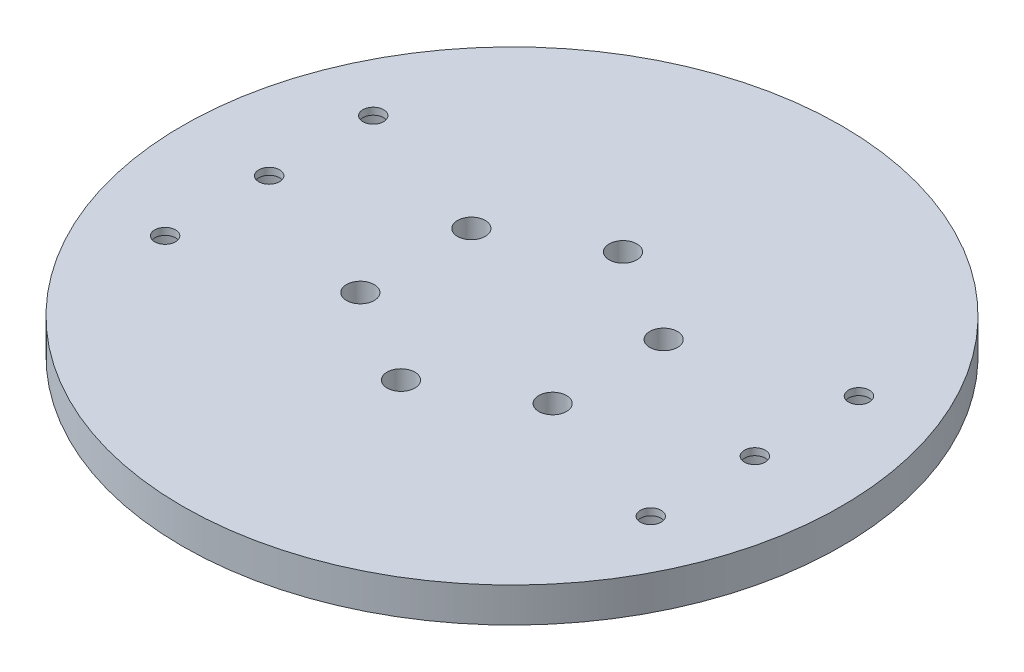
SolidWorks part; units mm, degrees
ref_plane "Alzado" through (0, 0, 0) normal (0, 0, 1) x (1, 0, 0)
ref_plane "Planta" through (0, 0, 0) normal (0, 1, 0) x (1, 0, 0)
ref_plane "Vista lateral" through (0, 0, 0) normal (1, 0, 0) x (0, 0, -1)
sketch "Croquis1" plane through (0, 0, 0) normal (0, 1, 0) x (1, 0, 0)
  circle A0 centre (0, 0) radius 24.5
  dimension "D1" = 49
extrude "Saliente-Extruir1" add sketch "Croquis1" along normal blind 4
sketch "Croquis2" plane through (0, 4, 0) normal (0, 1, 0) x (1, 0, 0)
  circle A0 centre (0, 0) radius 16 construction
  circle A1 centre (0, 16) radius 2
  dimension "D1" = 32
  dimension "D2" = 4
extrude "Cortar-Extruir1" cut sketch "Croquis2" against normal through all
pattern_circular "MatrizC1" count 6 over 360 about axis through (0, 0, 0) along (0, 1, 0) of "Cortar-Extruir1"
sketch "Croquis3" plane through (0, 4, 0) normal (0, 1, 0) x (1, 0, 0)
  circle A1 centre (0, 0) radius 47.5
  circle A2 centre (13.8564, 8) radius 2 construction
  circle A3 centre (13.8564, -8) radius 2 construction
  circle A4 centre (0, -16) radius 2 construction
  circle A5 centre (-13.8564, -8) radius 2 construction
  circle A6 centre (-13.8564, 8) radius 2 construction
  circle A7 centre (0, 16) radius 2 construction
  circle A8 centre (13.8564, 8) radius 2
  circle A9 centre (13.8564, -8) radius 2
  circle A10 centre (0, -16) radius 2
  circle A11 centre (-13.8564, -8) radius 2
  circle A12 centre (-13.8564, 8) radius 2
  circle A13 centre (0, 16) radius 2
  dimension "D1" = 95
extrude "Saliente-Extruir2" add sketch "Croquis3" along normal blind 5
sketch "Croquis4" plane through (0, 9, 0) normal (0, 1, 0) x (1, 0, 0)
  line L1 (-30, -20) -> (30, -20)
  line L2 (-30, -20) -> (-30, 20)
  line L3 (-30, 20) -> (30, 20)
  line L4 (30, -20) -> (30, 20)
  line L5 (-30, -20) -> (30, 20) construction
  line L6 (-30, 20) -> (30, -20) construction
  point P0 (0, 0)
  dimension "D1" = 40
  dimension "D2" = 60
sketch "Croquis6" plane through (0, 9, 0) normal (0, 1, 0) x (1, 0, 0)
  line L0 (-30, -20) -> (-35, -20) construction
  line L1 (-35, -20) -> (-35, 50) construction
  line L5 (-30, 20) -> (30, 20) construction
  circle A2 centre (-35, 15) radius 1.5
  circle A3 centre (-35, 0) radius 1.5
  circle A4 centre (-35, -15) radius 1.5
  dimension "D3" = 5
  dimension "D6" = 3
  dimension "D1" = 5
  dimension "D2" = 70
  dimension "D4" = 5
  dimension "D5" = 15
  dimension "D7" = 15
extrude "Cortar-Extruir2" cut sketch "Croquis6" against normal through all
mirror "Simetría1" about plane through (0, 0, 0) normal (1, 0, 0) of "Cortar-Extruir2"
sketch "Croquis7" plane through (0, 4, 0) normal (0, -1, 0) x (1, 0, 0)
  circle A0 centre (35, 15) radius 1.5 construction
  circle A1 centre (35, 0) radius 1.5 construction
  circle A2 centre (35, -15) radius 1.5 construction
  circle A5 centre (-35, -15) radius 1.5 construction
  circle A6 centre (-35, 0) radius 1.5 construction
  circle A7 centre (-35, 15) radius 1.5 construction
  circle A8 centre (35, 15) radius 1.5
  circle A9 centre (35, 0) radius 1.5
  circle A10 centre (35, -15) radius 1.5
  circle A13 centre (-35, -15) radius 1.5
  circle A14 centre (-35, 0) radius 1.5
  circle A15 centre (-35, 15) radius 1.5
  circle A16 centre (35, 15) radius 3.5
  circle A17 centre (35, 0) radius 3.5
  circle A18 centre (35, -15) radius 3.5
  circle A20 centre (-35, 15) radius 3.5
  circle A21 centre (-35, 0) radius 3.5
  circle A22 centre (-35, -15) radius 3.5
  dimension "D1" = 2
extrude "Cortar-Extruir3" cut sketch "Croquis7" against normal blind 4
